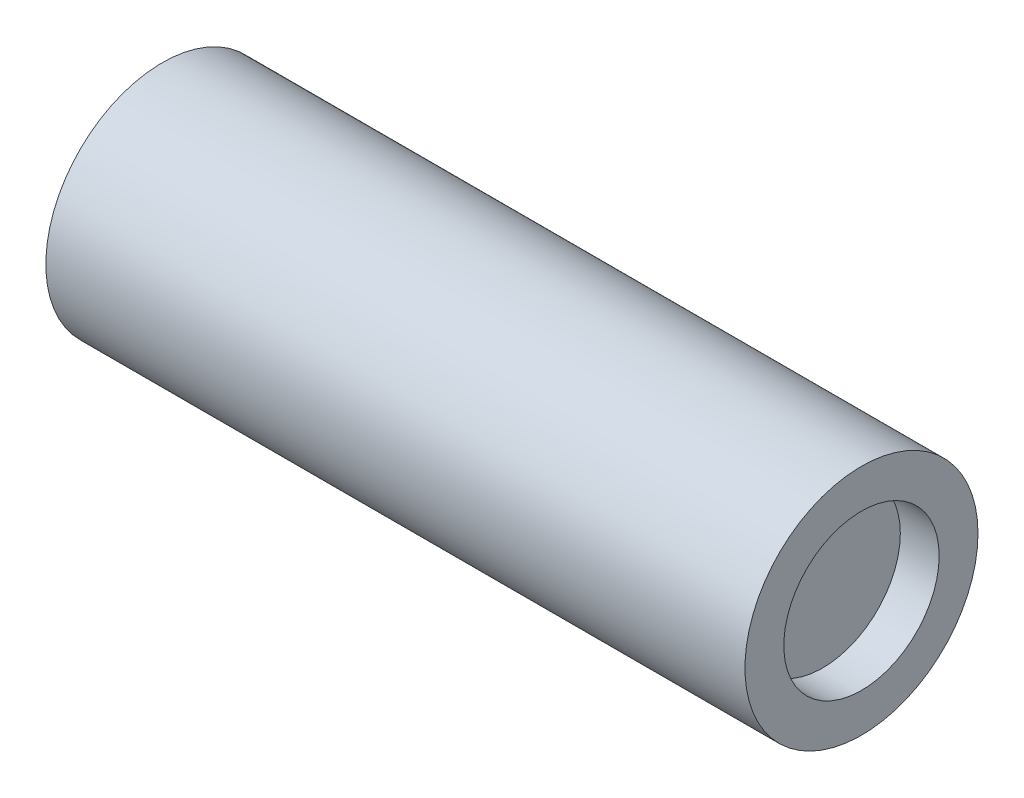
SolidWorks part; units mm, degrees
ref_plane "前视基准面" through (0, 0, 0) normal (0, 0, 1) x (1, 0, 0)
ref_plane "上视基准面" through (0, 0, 0) normal (0, 1, 0) x (1, 0, 0)
ref_plane "右视基准面" through (0, 0, 0) normal (1, 0, 0) x (0, 0, -1)
other "Configuration Table"
sketch "Sketch2" plane through (0, 0, 0) normal (1, 0, 0) x (0, 0, -1)
  circle A0 centre (0, 0) radius 6
extrude "Boss-Extrude1" add sketch "Sketch2" along normal blind 36
sketch "Sketch3" plane through (36, 0, 0) normal (1, 0, 0) x (0, 0, -1)
  circle A0 centre (0, 0) radius 4
extrude "Cut-Extrude1" cut sketch "Sketch3" against normal blind 2
sketch "Sketch4" plane through (0, 0, 0) normal (1, 0, 0) x (0, 0, -1)
  line L0 (0, 0) -> (0, 2.5157) construction
  circle A4 centre (0.51, 0) radius 0.5
  circle A5 centre (-0.51, 0) radius 0.5
  dimension "D1" = 0.51
extrude "Boss-Extrude4" add sketch "Sketch4" against normal blind 3
